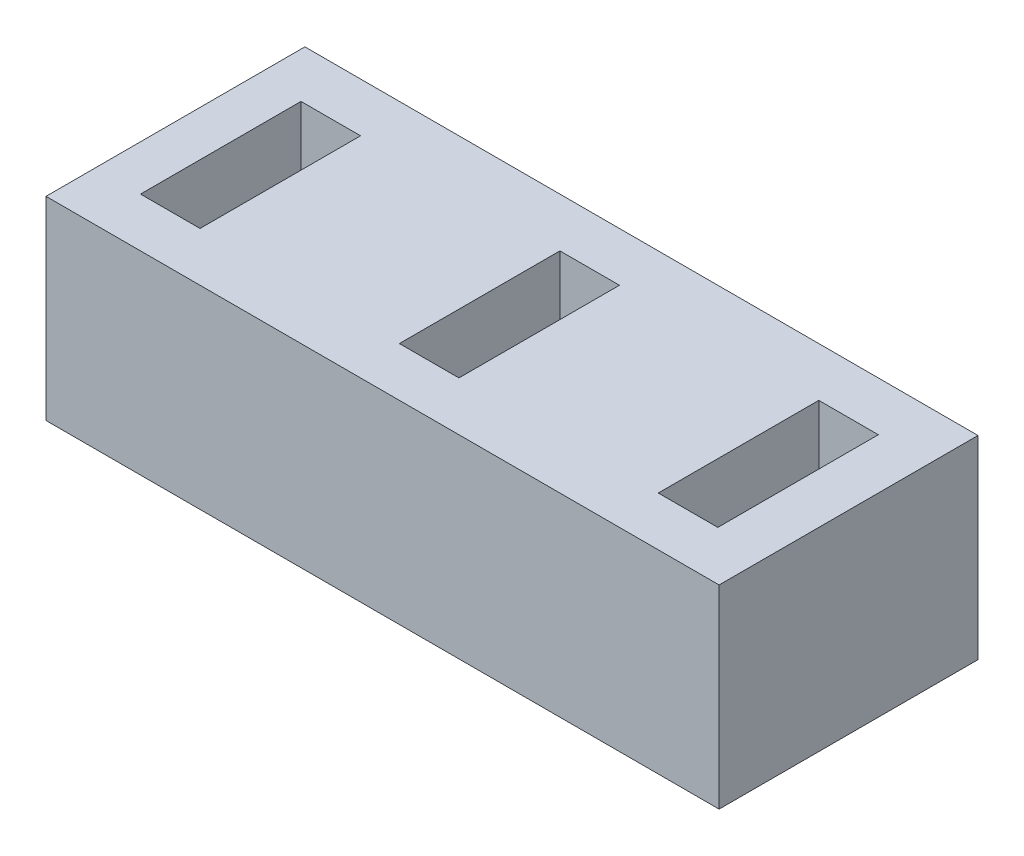
SolidWorks part; units mm, degrees
ref_plane "Alzado" through (0, 0, 0) normal (0, 0, 1) x (1, 0, 0)
ref_plane "Planta" through (0, 0, 0) normal (0, 1, 0) x (1, 0, 0)
ref_plane "Vista lateral" through (0, 0, 0) normal (1, 0, 0) x (0, 0, -1)
sketch "Croquis1" plane through (0, 0, 0) normal (0, 1, 0) x (1, 0, 0)
  line L0 (0, 0) -> (0, 20)
  line L1 (0, 20) -> (52, 20)
  line L2 (52, 20) -> (52, 0)
  line L3 (52, 0) -> (0, 0)
  point P3 (0, 0)
  dimension "D1" = 20
  dimension "D2" = 52
extrude "Saliente-Extruir1" add sketch "Croquis1" along normal blind 15 contours L3 L0 L1 L2
sketch "Croquis2" plane through (0, 15, 0) normal (0, 1, 0) x (1, 0, 0)
  line L0 (3.5, 16.2) -> (8.1, 16.2)
  line L1 (8.1, 16.2) -> (8.1, 3.8)
  line L2 (8.1, 3.8) -> (3.5, 3.8)
  line L3 (3.5, 3.8) -> (3.5, 16.2)
  line L4 (52, 0) -> (0, 0) construction
  line L5 (0, 0) -> (0, 20) construction
  line L6 (43.5, 16.2) -> (48.1, 16.2)
  line L7 (48.1, 16.2) -> (48.1, 3.8)
  line L8 (48.1, 3.8) -> (43.5, 3.8)
  line L9 (43.5, 3.8) -> (43.5, 16.2)
  line L10 (23.5, 16.2) -> (28.1, 16.2)
  line L11 (28.1, 16.2) -> (28.1, 3.8)
  line L12 (28.1, 3.8) -> (23.5, 3.8)
  line L13 (23.5, 3.8) -> (23.5, 16.2)
  dimension "D1" = 12.4
  dimension "D2" = 4.6
  dimension "D3" = 3.8
  dimension "D4" = 3.5
  dimension "D5" = 20
  dimension "D6" = 20
  dimension "D7" = 3.8
  dimension "D8" = 3.8
extrude "Cortar-Extruir1" cut sketch "Croquis2" against normal through all
